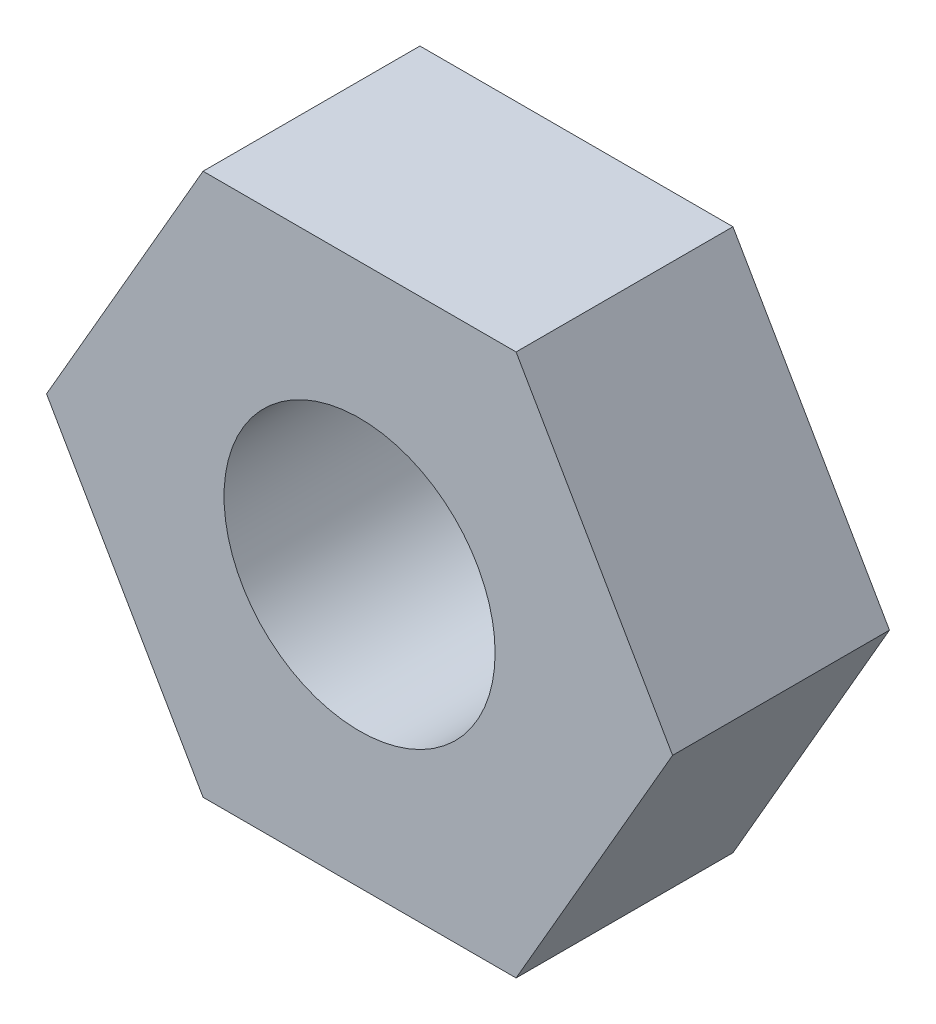
SolidWorks part; units mm, degrees
material "AISI 4340 Steel, normalized"
ref_plane "Front Plane" through (0, 0, 0) normal (0, 0, 1) x (1, 0, 0)
ref_plane "Top Plane" through (0, 0, 0) normal (0, 1, 0) x (1, 0, 0)
ref_plane "Right Plane" through (0, 0, 0) normal (1, 0, 0) x (0, 0, -1)
sketch "Sketch1" plane through (0, 0, 0) normal (0, 0, 1) x (1, 0, 0)
  line L0 (2.8868, 0) -> (1.4434, 2.5)
  line L1 (1.4434, 2.5) -> (-1.4434, 2.5)
  line L2 (-1.4434, 2.5) -> (-2.8868, 0)
  line L3 (-2.8868, 0) -> (-1.4434, -2.5)
  line L4 (-1.4434, -2.5) -> (1.4434, -2.5)
  line L5 (1.4434, -2.5) -> (2.8868, 0)
  circle A0 centre (0, 0) radius 1.25
extrude "Nut_Envelope" add sketch "Sketch1" along normal blind 2
